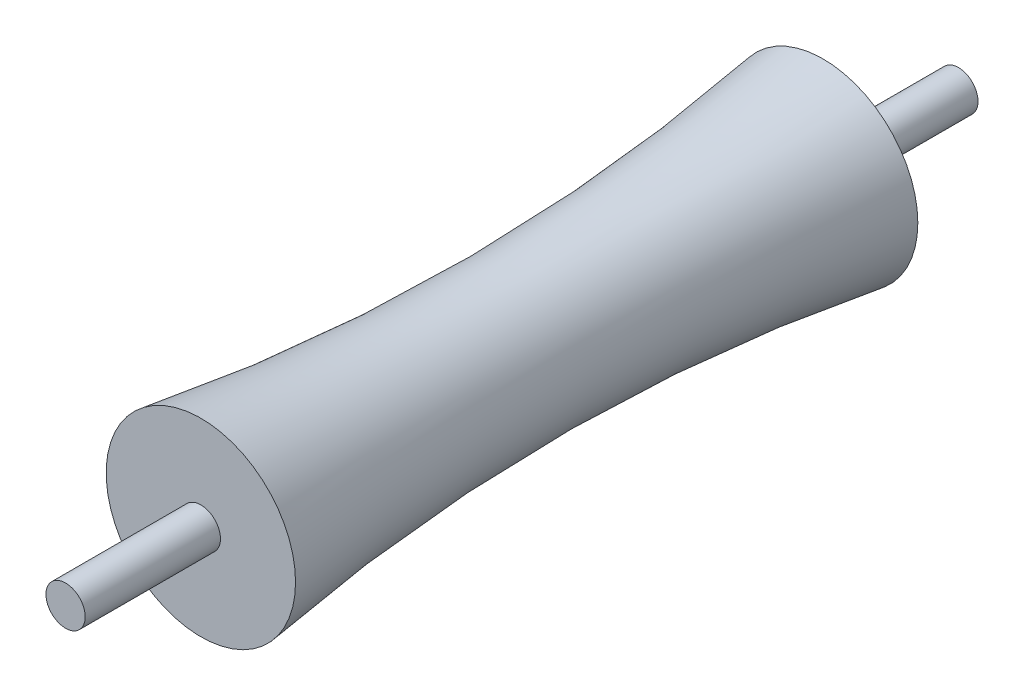
SolidWorks part; units mm, degrees
ref_plane "Front Plane" through (0, 0, 0) normal (0, 0, 1) x (1, 0, 0)
ref_plane "Top Plane" through (0, 0, 0) normal (0, 1, 0) x (1, 0, 0)
ref_plane "Right Plane" through (0, 0, 0) normal (1, 0, 0) x (0, 0, -1)
sketch "Sketch1" plane through (0, 0, 0) normal (0, 1, 0) x (1, 0, 0)
  line L0 (0, 0) -> (0, 46)
  line L1 (0, 46) -> (7, 46)
  line L2 (0, 0) -> (7, 0)
  arc A0 (7, 0) -> (7, 46) centre (155.2262, 23) cw
  dimension "D1" = 46
  dimension "D2" = 7
  dimension "D3" = 7
revolve "Revolve1" add sketch "Sketch1" angle 360 about L0
sketch "Sketch2" plane through (0, 0, 0) normal (0, 0, 1) x (1, 0, 0)
  circle A0 centre (0, 0) radius 1.45
extrude "Boss-Extrude1" add sketch "Sketch2" along normal blind 10
sketch "Sketch3" plane through (0, 0, -46) normal (0, 0, -1) x (-1, 0, 0)
  circle A0 centre (0, 0) radius 1.45
extrude "Boss-Extrude2" add sketch "Sketch3" along normal blind 10
